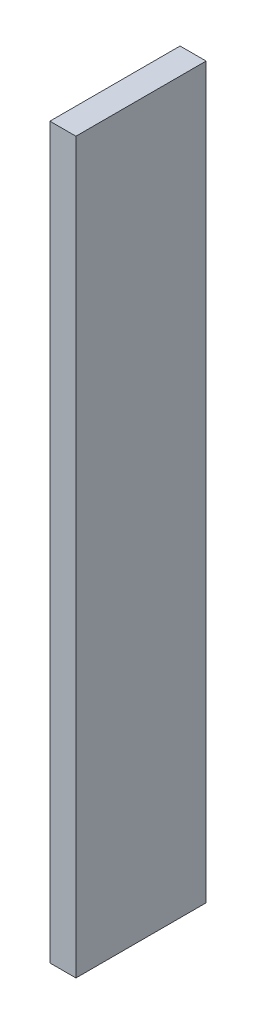
SolidWorks part; units mm, degrees
ref_plane "Plan de face" through (0, 0, 0) normal (0, 0, 1) x (1, 0, 0)
ref_plane "Plan de dessus" through (0, 0, 0) normal (0, 1, 0) x (1, 0, 0)
ref_plane "Plan de droite" through (0, 0, 0) normal (1, 0, 0) x (0, 0, -1)
sketch "Esquisse1" plane through (0, 0, 0) normal (1, 0, 0) x (0, 0, -1)
  line L1 (-25, -140) -> (25, -140)
  line L2 (-25, -140) -> (-25, 140)
  line L3 (-25, 140) -> (25, 140)
  line L4 (25, -140) -> (25, 140)
  line L5 (-25, -140) -> (25, 140) construction
  line L6 (-25, 140) -> (25, -140) construction
  point P0 (0, 0)
  dimension "D1" = 50
  dimension "D2" = 280
extrude "Boss.-Extru.1" add sketch "Esquisse1" along normal blind 10
